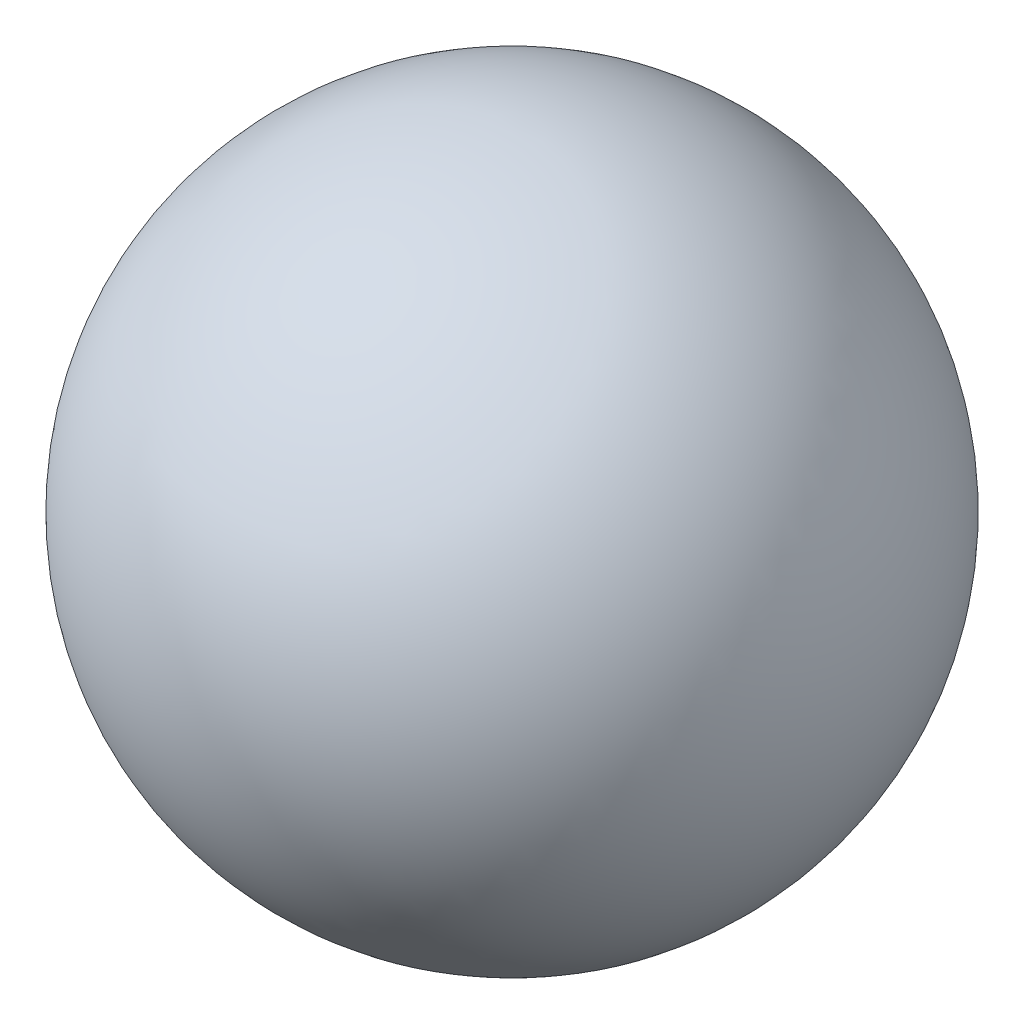
SolidWorks part; units mm, degrees
ref_plane "前视基准面" through (0, 0, 0) normal (0, 0, 1) x (1, 0, 0)
ref_plane "上视基准面" through (0, 0, 0) normal (0, 1, 0) x (1, 0, 0)
ref_plane "右视基准面" through (0, 0, 0) normal (1, 0, 0) x (0, 0, -1)
sketch "草图1" plane through (0, 0, 0) normal (0, 0, 1) x (1, 0, 0)
  line L0 (0, 7) -> (0, -7)
  arc A0 (0, -7) -> (0, 7) centre (0, 0) ccw
revolve "旋转1" add sketch "草图1" angle 360 about L0
